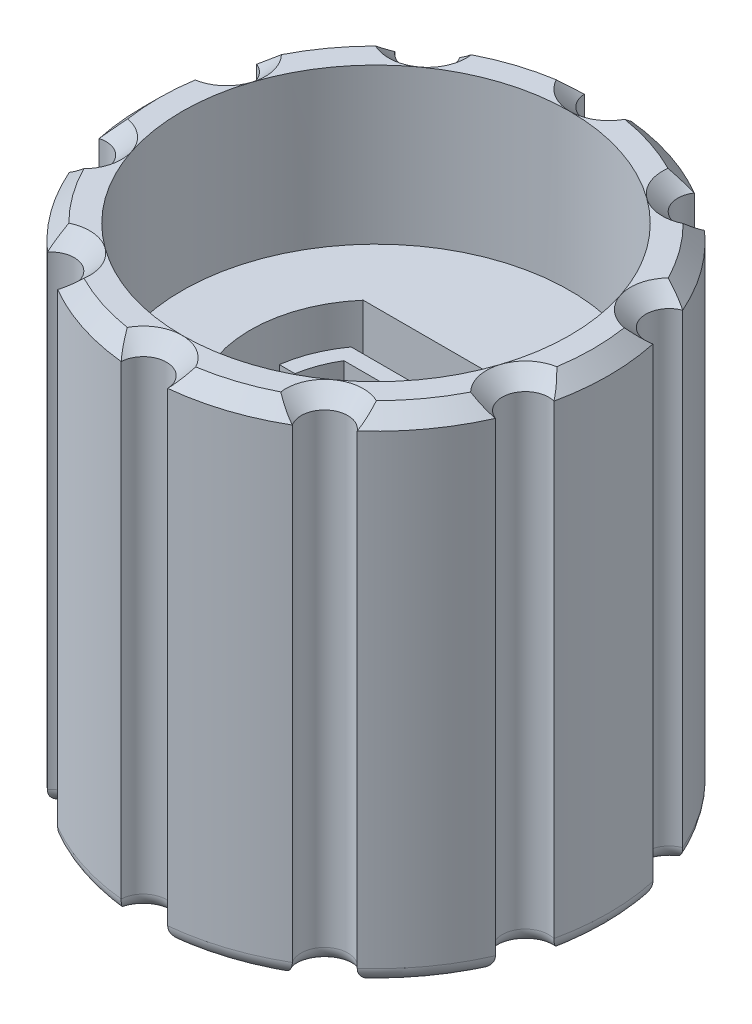
SolidWorks part; units mm, degrees
material "Custom Plastic"
ref_plane "Front Plane" through (0, 0, 0) normal (0, 0, 1) x (1, 0, 0)
ref_plane "Top Plane" through (0, 0, 0) normal (0, 1, 0) x (1, 0, 0)
ref_plane "Right Plane" through (0, 0, 0) normal (1, 0, 0) x (0, 0, -1)
sketch "Sketch1" plane through (0, 0, 0) normal (0, 1, 0) x (1, 0, 0)
  circle A0 centre (0, 0) radius 7.5
  dimension "D1" = 15
extrude "Boss-Extrude1" add sketch "Sketch1" along normal blind 16
sketch "Sketch4" plane through (0, 16, 0) normal (0, 1, 0) x (1, 0, 0)
  line L0 (0, 0) -> (0, -7.5) construction
  line L1 (0, 0) -> (4.4084, -6.0676) construction
  arc A0 (0.7491, -7.4625) -> (-0.7491, -7.4625) centre (0, -7.5) ccw
  circle A1 centre (0, 0) radius 7.5 construction
  circle A2 centre (0, 0) radius 7.5
  arc A3 (-3.7803, -6.4776) -> (-4.9924, -5.597) centre (-4.4084, -6.0676) ccw
  arc A4 (-6.8658, -3.0184) -> (-7.3287, -1.5936) centre (-7.1329, -2.3176) ccw
  arc A5 (-7.3287, 1.5936) -> (-6.8658, 3.0184) centre (-7.1329, 2.3176) ccw
  arc A6 (-4.9924, 5.597) -> (-3.7803, 6.4776) centre (-4.4084, 6.0676) ccw
  arc A7 (-0.7491, 7.4625) -> (0.7491, 7.4625) centre (0, 7.5) ccw
  arc A8 (3.7803, 6.4776) -> (4.9924, 5.597) centre (4.4084, 6.0676) ccw
  arc A9 (6.8658, 3.0184) -> (7.3287, 1.5936) centre (7.1329, 2.3176) ccw
  arc A10 (7.3287, -1.5936) -> (6.8658, -3.0184) centre (7.1329, -2.3176) ccw
  arc A11 (4.9924, -5.597) -> (3.7803, -6.4776) centre (4.4084, -6.0676) ccw
  point P37 (0, 0)
  circle M7 centre (0, 0) radius 7.5
  dimension "D1" = 1.5
  dimension "D3" = 36
  dimension "D2" = 10
extrude "Cut-Extrude3" cut sketch "Sketch4" against normal through all contours A2 A6 | A2 A7 | A2 A8 | A2 A9 | A2 A10 | A2 A11 | A0 M7 | A2 A3 | A2 A4 | A2 A5
chamfer "Chamfer1" distance 0.5 angle 45 20 edges at (-3.9676, 16, 5.4609) (-6.0676, 16, 4.4084) (-6.4196, 16, 2.0859) (-7.5, 16, 0) (-6.4196, 16, -2.0859) (-6.0676, 16, -4.4084) (-3.9676, 16, -5.4609) (-2.3176, 16, -7.1329) (0, 16, -6.75) (2.3176, 16, -7.1329) (3.9676, 16, -5.4609) (6.0676, 16, -4.4084) (6.4196, 16, -2.0859) (7.5, 16, 0) (6.4196, 16, 2.0859) (6.0676, 16, 4.4084) (3.9676, 16, 5.4609) (2.3176, 16, 7.1329) (0, 16, 6.75) (-2.3176, 16, 7.1329)
fillet "Fillet1" radius 0.5 20 edges at (-3.9676, 0, 5.4609) (-2.3176, 0, 7.1329) (0, 0, 6.75) (2.3176, 0, 7.1329) (3.9676, 0, 5.4609) (6.0676, 0, 4.4084) (6.4196, 0, 2.0859) (7.5, 0, 0) (6.4196, 0, -2.0859) (6.0676, 0, -4.4084) (3.9676, 0, -5.4609) (2.3176, 0, -7.1329) (0, 0, -6.75) (-2.3176, 0, -7.1329) (-3.9676, 0, -5.4609) (-6.0676, 0, -4.4084) (-6.4196, 0, -2.0859) (-7.5, 0, 0) (-6.4196, 0, 2.0859) (-6.0676, 0, 4.4084)
sketch "Sketch5" plane through (0, 16, 0) normal (0, 1, 0) x (1, 0, 0)
  line L1 (-3.0627, 2.65) -> (3.0627, 2.65)
  arc A1 (-3.0627, 2.65) -> (3.0627, 2.65) centre (0, 0) ccw
  point P8 (0, -4.05)
  dimension "D1" = 8.1
  dimension "D2" = 6.7
extrude "Cut-Extrude4" cut sketch "Sketch5" against normal blind 14
sketch "Sketch6" plane through (0, 2, 0) normal (0, 1, 0) x (1, 0, 0)
  line L0 (2.9496, 2.15) -> (-2.9496, 2.15)
  line L3 (2.6833, 1.65) -> (-2.6833, 1.65)
  line L4 (-3.6156, 0.5) -> (-3.1101, 0.5)
  line L5 (-3.65, 0) -> (-3.15, 0)
  line L6 (-4.05, 0) -> (4.05, 0) construction
  line L8 (3.1101, 0.5) -> (3.6156, 0.5)
  line L9 (-4.05, 0.5) -> (4.05, 0.5) construction
  line L10 (3.15, 0) -> (3.65, 0)
  arc A0 (-2.9496, 2.15) -> (-3.6156, 0.5) centre (0, 0) ccw
  arc A3 (-2.6833, 1.65) -> (-3.1101, 0.5) centre (0, 0) ccw
  arc A6 (3.6156, 0.5) -> (2.9496, 2.15) centre (0, 0) ccw
  arc A7 (-2.9496, 2.15) -> (2.9496, 2.15) centre (0, 0) ccw construction
  arc A8 (3.1101, 0.5) -> (2.6833, 1.65) centre (0, 0) ccw
  arc A9 (-2.6833, 1.65) -> (2.6833, 1.65) centre (0, 0) ccw construction
  arc A10 (-3.15, 0) -> (3.15, 0) centre (0, 0) ccw
  arc A11 (-3.65, 0) -> (3.65, 0) centre (0, 0) ccw
  dimension "D1" = 3.65
  dimension "D2" = 3.15
  dimension "D5" = 2.15
  dimension "D6" = 0.5
  dimension "D3" = 0.5
  dimension "D4" = 0.5
extrude "Boss-Extrude2" add sketch "Sketch6" along normal blind 8
sketch "Sketch7" plane through (0, 16, 0) normal (0, 1, 0) x (1, 0, 0)
  line L0 (3.0627, 2.65) -> (-3.0627, 2.65) construction
  line L1 (3.0627, 2.65) -> (-3.0627, 2.65)
  circle A0 centre (0, 0) radius 6.25
  arc A1 (-3.0627, 2.65) -> (3.0627, 2.65) centre (0, 0) ccw construction
  arc A2 (-3.0627, 2.65) -> (3.0627, 2.65) centre (0, 0) ccw
  dimension "D1" = 12.5
extrude "Cut-Extrude5" cut sketch "Sketch7" against normal blind 5
